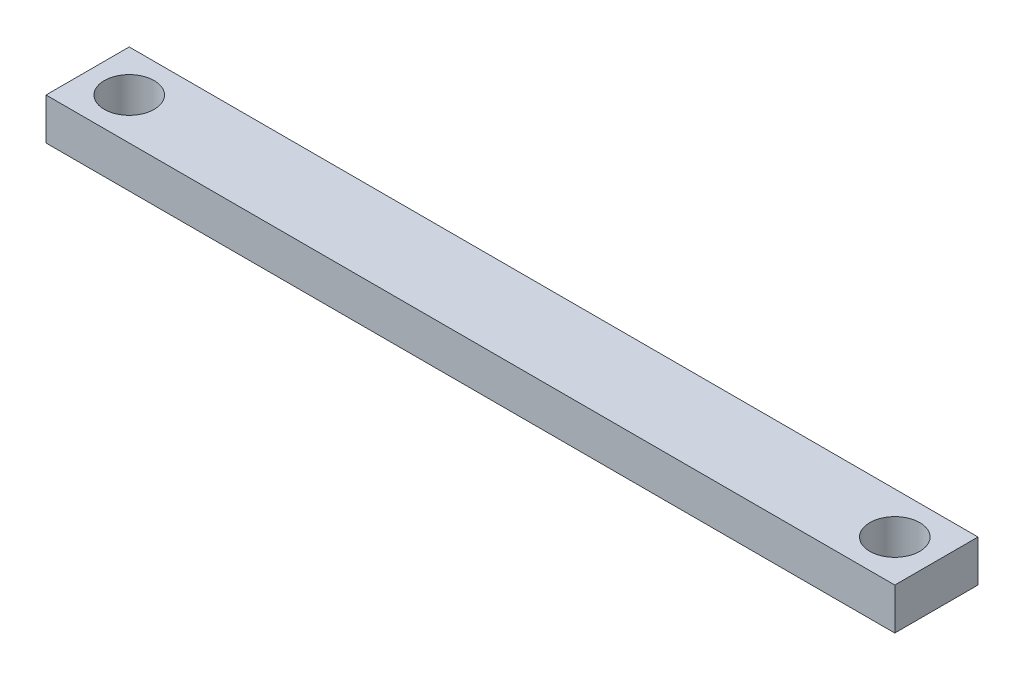
SolidWorks part; units mm, degrees
ref_plane "Front Plane" through (0, 0, 0) normal (0, 0, 1) x (1, 0, 0)
ref_plane "Top Plane" through (0, 0, 0) normal (0, 1, 0) x (1, 0, 0)
ref_plane "Right Plane" through (0, 0, 0) normal (1, 0, 0) x (0, 0, -1)
sketch "Sketch1" plane through (0, 0, 0) normal (0, 1, 0) x (1, 0, 0)
  line L1 (51, 5) -> (-51, 5)
  line L2 (51, 5) -> (51, -5)
  line L3 (51, -5) -> (-51, -5)
  line L4 (-51, 5) -> (-51, -5)
  line L5 (51, 5) -> (-51, -5) construction
  line L6 (51, -5) -> (-51, 5) construction
  circle A0 centre (-46, 0) radius 3
  circle A1 centre (46, 0) radius 3
  point P0 (0, 0)
  dimension "D3" = 6
  dimension "D1" = 10
  dimension "D2" = 102
  dimension "D4" = 5
  dimension "D5" = 5
  dimension "D6" = 92
extrude "Boss-Extrude1" add sketch "Sketch1" along normal mid plane 5
equation "\"D2@Sketch1\"= \"D6@Sketch1\" + 10mm"
